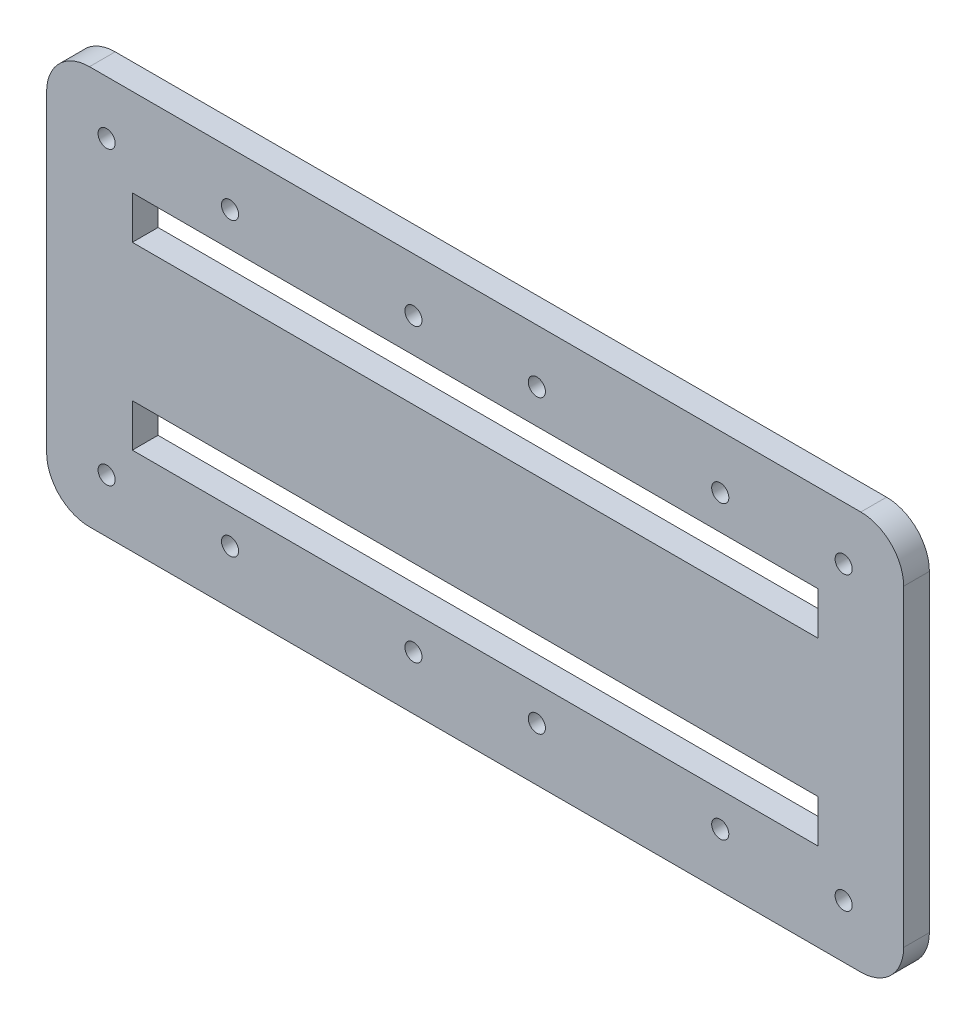
SolidWorks part; units mm, degrees
ref_plane "前基準面" through (0, 0, 0) normal (0, 0, 1) x (1, 0, 0)
ref_plane "上基準面" through (0, 0, 0) normal (0, 1, 0) x (1, 0, 0)
ref_plane "右基準面" through (0, 0, 0) normal (1, 0, 0) x (0, 0, -1)
sketch "草圖1" plane through (0, 0, 0) normal (0, 0, 1) x (1, 0, 0)
  line L1 (-70.83, 54.7396) -> (-270.83, 54.7396)
  line L2 (-70.83, 54.7396) -> (-70.83, 147.7396)
  line L3 (-70.83, 147.7396) -> (-270.83, 147.7396)
  line L4 (-270.83, 54.7396) -> (-270.83, 147.7396)
  line L5 (-250.83, 127.2396) -> (-90.83, 127.2396)
  line L6 (-250.83, 127.2396) -> (-250.83, 117.2396)
  line L7 (-250.83, 117.2396) -> (-90.83, 117.2396)
  line L8 (-90.83, 127.2396) -> (-90.83, 117.2396)
  line L9 (-250.83, 85.2396) -> (-90.83, 85.2396)
  line L10 (-250.83, 85.2396) -> (-250.83, 75.2396)
  line L11 (-250.83, 75.2396) -> (-90.83, 75.2396)
  line L12 (-90.83, 85.2396) -> (-90.83, 75.2396)
  point P12 (-170.83, 127.2396)
  point P13 (-170.83, 147.7396)
  point P14 (-170.83, 85.2396)
  point P15 (-170.83, 117.2396)
  dimension "D1" = 93
  dimension "D2" = 200
  dimension "D3" = 160
  dimension "D4" = 0
  dimension "D5" = 0
  dimension "D6" = 160
  dimension "D7" = 10
  dimension "D8" = 10
  dimension "D9" = 20.5
  dimension "D10" = 20.5
extrude "填料-伸長1" add sketch "草圖1" along normal blind 6
sketch "草圖2" plane through (0, 0, 0) normal (0, 0, -1) x (-1, 0, 0)
  line L0 (70.83, 147.7396) -> (270.83, 147.7396) construction
  line L1 (70.83, 54.7396) -> (70.83, 147.7396) construction
  line L3 (70.83, 147.7396) -> (270.83, 147.7396) construction
  circle A0 centre (84.83, 135.2396) radius 2
  circle A1 centre (113.63, 135.2396) radius 2
  circle A2 centre (156.43, 135.2396) radius 2
  circle A3 centre (185.23, 135.2396) radius 2
  circle A4 centre (228.03, 135.2396) radius 2
  circle A5 centre (256.83, 135.2396) radius 2
  circle A6 centre (84.83, 67.2396) radius 2
  circle A7 centre (113.63, 67.2396) radius 2
  circle A8 centre (156.43, 67.2396) radius 2
  circle A9 centre (185.23, 67.2396) radius 2
  circle A10 centre (228.03, 67.2396) radius 2
  circle A11 centre (256.83, 67.2396) radius 2
  dimension "D1" = 12.5
  dimension "D2" = 4
  dimension "D3" = 14
  dimension "D4" = 4
  dimension "D5" = 28.8
  dimension "D8" = 12.5
  dimension "D6" = 3
  dimension "D7" = 2
extrude "除料-伸長1" cut sketch "草圖2" against normal up to surface (6 mm away) up to face at (-170.83, 101.2396, 6)
fillet "圓角1" radius 10 4 edges at (-270.83, 54.7396, 3) (-270.83, 147.7396, 3) (-70.83, 54.7396, 3) (-70.83, 147.7396, 3)
